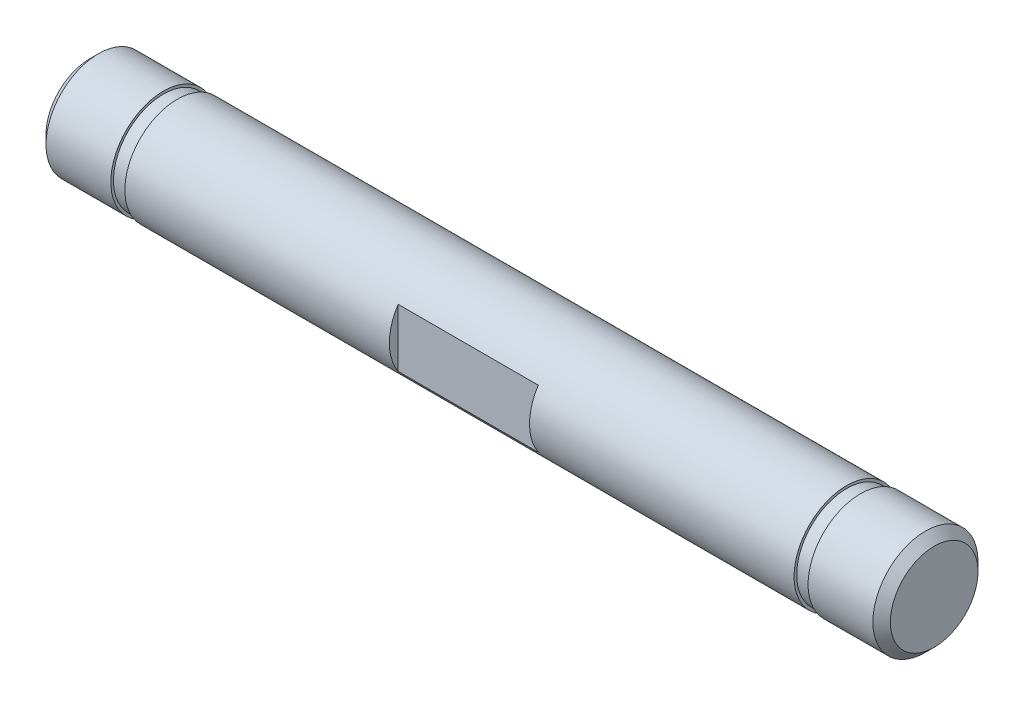
SolidWorks part; units mm, degrees
ref_plane "Alzado" through (0, 0, 0) normal (1, 0, 0) x (0, 1, 0)
ref_plane "Planta" through (0, 0, 0) normal (0, 0, 1) x (0, 1, 0)
ref_plane "Vista lateral" through (0, 0, 0) normal (0, 1, 0) x (-1, 0, 0)
sketch "Croquis1" plane through (0, 0, 0) normal (0, 1, 0) x (-1, 0, 0)
  line L1 (-19.1, 3) -> (19.1, 3)
  line L6 (24.1, 3) -> (24.1, 0)
  line L7 (-24.1, 0) -> (24.1, 0) construction
  line L23 (19.1, 3) -> (19.1, 2.85)
  line L24 (19.1, 2.85) -> (19.9, 2.85)
  line L25 (19.9, 2.85) -> (19.9, 3)
  line L26 (19.9, 3) -> (24.1, 3)
  line L27 (0, 0) -> (0, 3) construction
  line L28 (-19.9, 3) -> (-24.1, 3)
  line L29 (-19.9, 2.85) -> (-19.9, 3)
  line L30 (-19.1, 2.85) -> (-19.9, 2.85)
  line L31 (-19.1, 3) -> (-19.1, 2.85)
  line L32 (-24.1, 3) -> (-24.1, 0)
  line L33 (-24.1, 0) -> (24.1, 0)
  dimension "D2" = 6
  dimension "D1" = 5
  dimension "D4" = 0.8
  dimension "D3" = 38.2
  dimension "D5" = 5.7
revolve "Revolución1" add sketch "Croquis1" angle 360 about L7
sketch "Croquis2" plane through (0, 0, 0) normal (1, 0, 0) x (0, 1, 0)
  line L1 (1.6583, 2.5) -> (-1.6583, 2.5)
  circle A0 centre (0, 0) radius 3 construction
  circle A1 centre (0, 0) radius 3
  arc A3 (1.6583, 2.5) -> (-1.6583, 2.5) centre (0, 0) ccw
  point P4 (0, 3)
  dimension "D2" = 0.5
  dimension "D1" = 0
extrude "Cortar-Extruir1" cut sketch "Croquis2" against normal mid plane 8
chamfer "Chaflán1" distance 0.5 angle 45 2 edges at (-24.1, 0, -3) (24.1, 0, -3)
equation "\"ancho_circlip\"=0.8"
equation "\"ranura_circlip\"=0.45"
equation "\"d_circlip\"=5.7"
equation "\"D5@Croquis1\"=\"d_circlip\""
